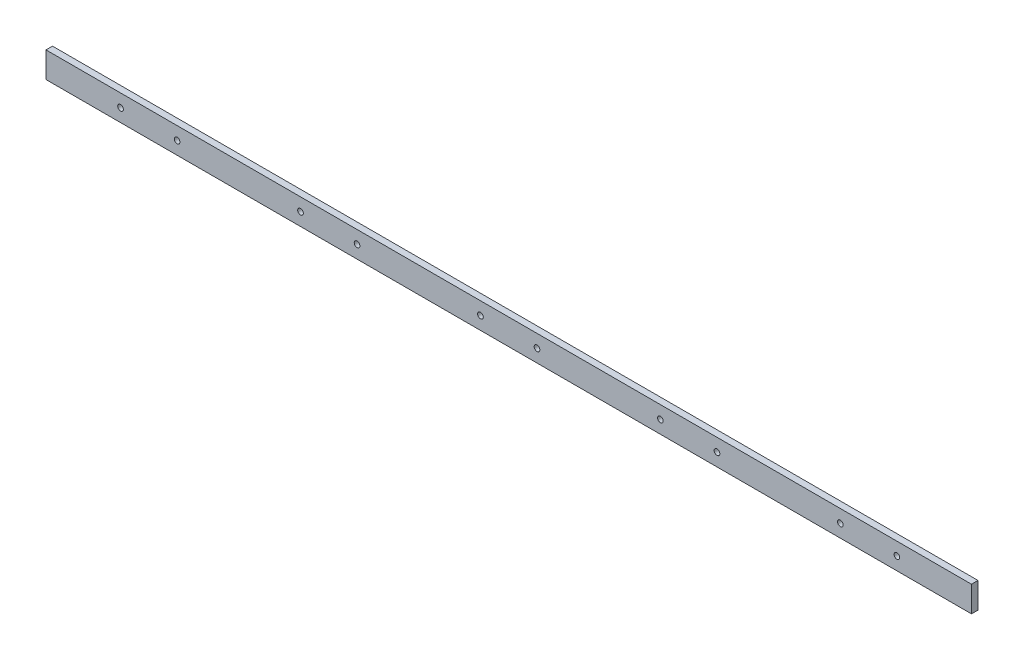
SolidWorks part; units mm, degrees
material "Acrylic (Medium-high impact)"
ref_plane "Front Plane" through (0, 0, 0) normal (0, 0, 1) x (1, 0, 0)
ref_plane "Top Plane" through (0, 0, 0) normal (0, 1, 0) x (1, 0, 0)
ref_plane "Right Plane" through (0, 0, 0) normal (1, 0, 0) x (0, 0, -1)
sketch "Sketch1" plane through (0, 0, 0) normal (0, 0, 1) x (1, 0, 0)
  line L1 (0, 0) -> (900, 0)
  line L2 (0, 0) -> (0, 25)
  line L3 (0, 25) -> (900, 25)
  line L4 (900, 0) -> (900, 25)
  dimension "D1" = 900
  dimension "D2" = 25
extrude "Boss-Extrude1" add sketch "Sketch1" along normal blind 6.35
ref_plane "Plane1" through (0, 12.5, 0) normal (0, -1, 0) x (-1, 0, 0)
ref_plane "Plane2" through (450, 0, 0) normal (1, 0, 0) x (0, 0, -1)
sketch "Sketch2" plane through (0, 0, 6.35) normal (0, 0, 1) x (1, 0, 0)
  line L0 (450, 25) -> (450, 0) construction
  line L1 (900, 25) -> (0, 25) construction
  line L2 (0, 0) -> (900, 0) construction
  line L3 (477.5, 12.5) -> (422.5, 12.5) construction
  line L4 (477.5, 12.5) -> (652.5, 12.5) construction
  circle A0 centre (477.5, 12.5) radius 2.75
  circle A1 centre (422.5, 12.5) radius 2.75
  circle A2 centre (652.5, 12.5) radius 2.75
  circle A3 centre (597.5, 12.5) radius 2.75
  circle A4 centre (827.5, 12.5) radius 2.75
  circle A5 centre (772.5, 12.5) radius 2.75
  circle A6 centre (127.5, 12.5) radius 2.75
  circle A7 centre (72.5, 12.5) radius 2.75
  circle A8 centre (247.5, 12.5) radius 2.75
  circle A9 centre (302.5, 12.5) radius 2.75
  point P8 (450, 12.5)
  point P9 (450, 12.5)
  dimension "D2" = 5.5
  dimension "D1" = 55
  dimension "D4" = 175
  dimension "D3" = 3
extrude "Cut-Extrude1" cut sketch "Sketch2" against normal up to next
